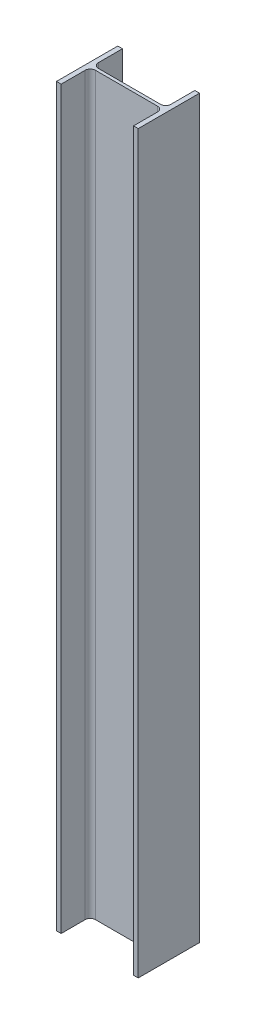
SolidWorks part; units mm, degrees
material "Plain Carbon Steel"
ref_plane "Front Plane" through (0, 0, 0) normal (0, 0, 1) x (1, 0, 0)
ref_plane "Top Plane" through (0, 0, 0) normal (0, 1, 0) x (1, 0, 0)
ref_plane "Right Plane" through (0, 0, 0) normal (1, 0, 0) x (0, 0, -1)
sketch3d "3DSketch1"
  line L1 (3.175, -457.2, -609.6) -> (3.175, -457.2, 0) construction
  line L2 (-3.175, -457.2, 0) -> (3.175, -457.2, 0) construction
  line L3 (53.975, -457.2, -38.1) -> (53.975, 457.2, -38.1)
  point P0 (53.975, -457.2, -38.1)
  point P6 (53.975, 457.2, -38.1)
  dimension "D1" = 50.8
  dimension "D2" = 38.1
other "Al i beam AL I BEAM 4X2.31(1)"
ref_plane "Plane1" through (53.975, -457.2, -38.1) normal (0, 1, 0) x (0, 0, -1)
sketch "Sketch11" plane through (53.975, -457.2, -38.1) normal (0, 1, 0) x (0, 0, -1)
  line L0 (-38.1, -50.8) -> (-38.1, -44.958)
  line L1 (-38.1, -44.958) -> (-8.255, -44.958)
  line L2 (-1.905, -38.608) -> (-1.905, 38.608)
  line L3 (-8.255, 44.958) -> (-38.1, 44.958)
  line L4 (-38.1, 44.958) -> (-38.1, 50.8)
  line L5 (-38.1, 50.8) -> (38.1, 50.8)
  line L6 (38.1, 50.8) -> (38.1, 44.958)
  line L7 (38.1, 44.958) -> (8.255, 44.958)
  line L8 (1.905, 38.608) -> (1.905, -38.608)
  line L9 (8.255, -44.958) -> (38.1, -44.958)
  line L10 (38.1, -44.958) -> (38.1, -50.8)
  line L11 (38.1, -50.8) -> (-38.1, -50.8)
  line L12 (1.905, 0) -> (-1.905, 0) construction
  arc A0 (-8.255, -44.958) -> (-1.905, -38.608) centre (-8.255, -38.608) ccw
  arc A1 (-1.905, 38.608) -> (-8.255, 44.958) centre (-8.255, 38.608) ccw
  arc A2 (8.255, 44.958) -> (1.905, 38.608) centre (8.255, 38.608) ccw
  arc A3 (1.905, -38.608) -> (8.255, -44.958) centre (8.255, -38.608) ccw
  point P20 (0, 50.8)
  point P23 (0.282, 0)
  point P25 (0, -50.8)
  point P26 (0, 0)
  dimension "Ri" = 6.35
  dimension "Tw" = 3.81
  dimension "Bf" = 76.2
  dimension "Depth" = 101.6
  dimension "Tf" = 5.842
